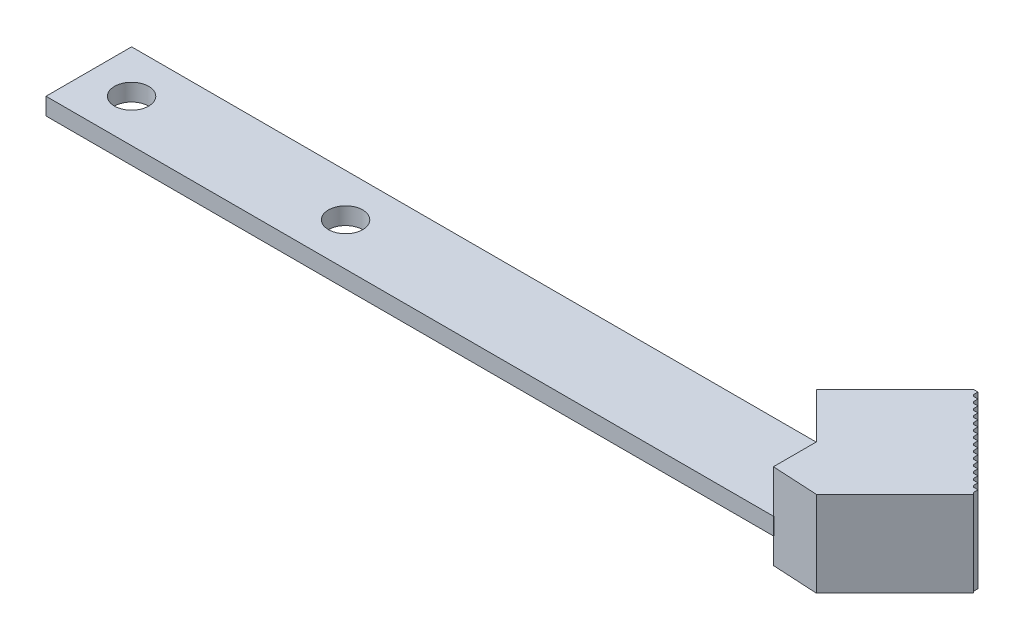
SolidWorks part; units mm, degrees
ref_plane "Front Plane" through (0, 0, 0) normal (0, 0, 1) x (1, 0, 0)
ref_plane "Top Plane" through (0, 0, 0) normal (0, 1, 0) x (1, 0, 0)
ref_plane "Right Plane" through (0, 0, 0) normal (1, 0, 0) x (0, 0, -1)
sketch "Sketch1" plane through (0, 0, 0) normal (0, 1, 0) x (1, 0, 0)
  line L1 (-24.2292, 7.0539) -> (60.7708, 7.0539)
  line L2 (-24.2292, 7.0539) -> (-24.2292, -2.9461)
  line L3 (-24.2292, -2.9461) -> (60.7708, -2.9461)
  line L4 (60.7708, 7.0539) -> (60.7708, -2.9461)
  circle A0 centre (-19.2292, 2.0539) radius 2
  circle A2 centre (5.7708, 2.0539) radius 2
  dimension "D3" = 5
  dimension "D5" = 25
  dimension "D1" = 10
  dimension "D2" = 85
extrude "Boss-Extrude1" add sketch "Sketch1" along normal blind 2
sketch "Sketch2" plane through (0, 2, 0) normal (0, 1, 0) x (1, 0, 0)
  line L0 (60.7708, 2.0539) -> (55.7708, 7.0539)
  line L1 (60.7708, -2.9461) -> (60.7708, 7.0539) construction
  line L2 (60.7708, 7.0539) -> (-24.2292, 7.0539) construction
  line L3 (55.7708, 7.0539) -> (60.7708, 7.0539)
  line L4 (60.7708, 7.0539) -> (60.7708, 2.0539)
  line L5 (60.7708, 2.0539) -> (60.7612, 2.0468)
  line M5 (60.7708, -2.9461) -> (60.7708, 7.0539)
  line M6 (60.7708, 7.0539) -> (-24.2292, 7.0539)
  dimension "D1" = 135
extrude "Cut-Extrude1" cut sketch "Sketch2" against normal blind 10 contours L0 M5 M6
sketch "Sketch3" plane through (31.4124, 0, -31.4124) normal (0.7071, 0, -0.7071) x (-0.7071, 0, -0.7071)
  line L1 (-33.9203, 6.9526) -> (-48.9203, 6.9526)
  line L2 (-33.9203, 6.9526) -> (-33.9203, -3.0474)
  line L3 (-33.9203, -3.0474) -> (-48.9203, -3.0474)
  line L4 (-48.9203, 6.9526) -> (-48.9203, -3.0474)
  dimension "D1" = 10
  dimension "D2" = 15
extrude "Boss-Extrude2" add sketch "Sketch3" along normal blind 13
sketch "Sketch4" plane through (0, 6.9526, 0) normal (0, 1, 0) x (1, 0, 0)
  line L0 (60.701, 2.1238) -> (60.701, -2.891)
  line L1 (55.3977, 7.4271) -> (66.0043, -3.1795) construction
  line L2 (60.701, -2.891) -> (66.0043, -3.1795)
  line L3 (66.0043, -3.1795) -> (60.701, 2.1238)
extrude "Boss-Extrude3" add sketch "Sketch4" against normal blind 10
sketch "Sketch6" plane through (0, 6.9526, 0) normal (0, 1, 0) x (1, 0, 0)
  line L0 (64.5901, 16.6195) -> (65.0901, 16.6195)
  line L1 (65.0901, 16.6195) -> (65.0901, 16.1195)
  line L2 (64.5901, 16.6195) -> (75.1967, 6.0129) construction
  line L3 (65.0901, 16.1195) -> (64.5901, 16.6195)
  line L4 (65.2972, 15.9124) -> (65.7972, 15.9124)
  line L5 (65.7972, 15.9124) -> (65.7972, 15.4124)
  line L6 (65.7972, 15.4124) -> (65.2972, 15.9124)
  line L7 (66.0043, 15.2053) -> (66.5043, 15.2053)
  line L8 (66.5043, 15.2053) -> (66.5043, 14.7053)
  line L9 (66.5043, 14.7053) -> (66.0043, 15.2053)
  line L10 (66.7114, 14.4982) -> (67.2114, 14.4982)
  line L11 (67.2114, 14.4982) -> (67.2114, 13.9982)
  line L12 (67.2114, 13.9982) -> (66.7114, 14.4982)
  line L13 (67.4185, 13.791) -> (67.9185, 13.791)
  line L14 (67.9185, 13.791) -> (67.9185, 13.291)
  line L15 (67.9185, 13.291) -> (67.4185, 13.791)
  line L16 (68.1256, 13.0839) -> (68.6256, 13.0839)
  line L17 (68.6256, 13.0839) -> (68.6256, 12.5839)
  line L18 (68.6256, 12.5839) -> (68.1256, 13.0839)
  line L19 (68.8327, 12.3768) -> (69.3327, 12.3768)
  line L20 (69.3327, 12.3768) -> (69.3327, 11.8768)
  line L21 (69.3327, 11.8768) -> (68.8327, 12.3768)
  line L22 (69.5398, 11.6697) -> (70.0398, 11.6697)
  line L23 (70.0398, 11.6697) -> (70.0398, 11.1697)
  line L24 (70.0398, 11.1697) -> (69.5398, 11.6697)
  line L25 (70.2469, 10.9626) -> (70.7469, 10.9626)
  line L26 (70.7469, 10.9626) -> (70.7469, 10.4626)
  line L27 (70.7469, 10.4626) -> (70.2469, 10.9626)
  line L28 (70.954, 10.2555) -> (71.454, 10.2555)
  line L29 (71.454, 10.2555) -> (71.454, 9.7555)
  line L30 (71.454, 9.7555) -> (70.954, 10.2555)
  line L31 (71.6611, 9.5484) -> (72.1611, 9.5484)
  line L32 (72.1611, 9.5484) -> (72.1611, 9.0484)
  line L33 (72.1611, 9.0484) -> (71.6611, 9.5484)
  line L34 (72.3682, 8.8413) -> (72.8682, 8.8413)
  line L35 (72.8682, 8.8413) -> (72.8682, 8.3413)
  line L36 (72.8682, 8.3413) -> (72.3682, 8.8413)
  line L37 (73.0753, 8.1342) -> (73.5753, 8.1342)
  line L38 (73.5753, 8.1342) -> (73.5753, 7.6342)
  line L39 (73.5753, 7.6342) -> (73.0753, 8.1342)
  line L40 (73.7824, 7.4271) -> (74.2824, 7.4271)
  line L41 (74.2824, 7.4271) -> (74.2824, 6.9271)
  line L42 (74.2824, 6.9271) -> (73.7824, 7.4271)
  line L43 (74.4896, 6.72) -> (74.9896, 6.72)
  line L44 (74.9896, 6.72) -> (74.9896, 6.22)
  line L45 (74.9896, 6.22) -> (74.4896, 6.72)
  dimension "D1" = 0.5
  dimension "D2" = 15
extrude "Boss-Extrude4" add sketch "Sketch6" against normal blind 10
